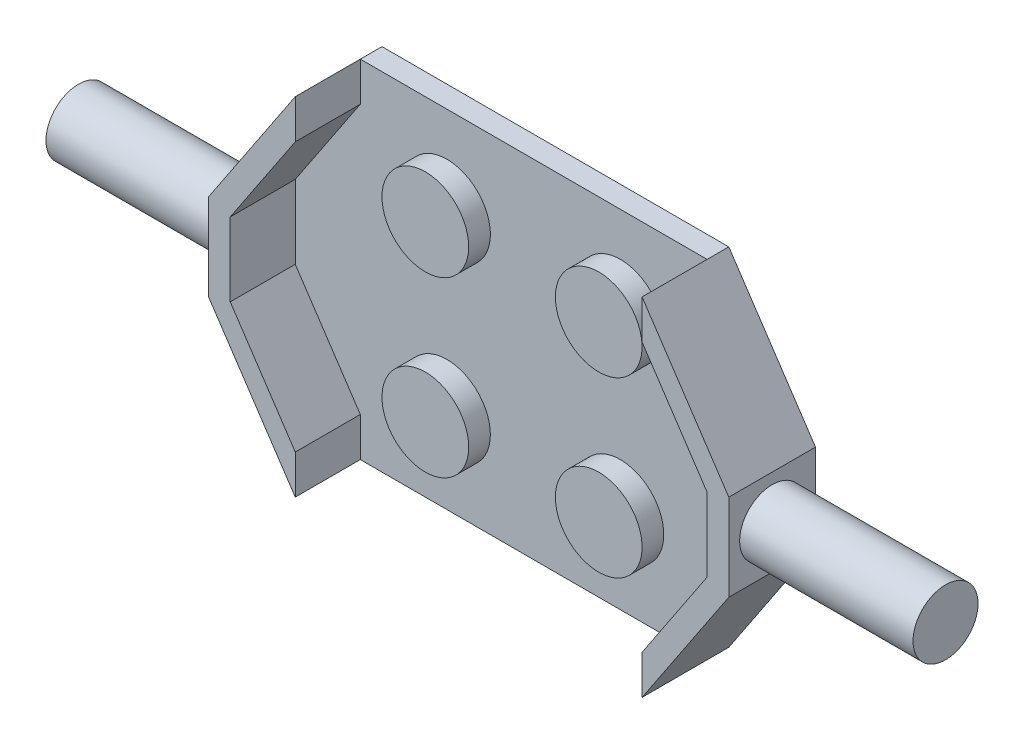
SolidWorks part; units mm, degrees
ref_plane "Front Plane" through (0, 0, 0) normal (0, 0, 1) x (1, 0, 0)
ref_plane "Top Plane" through (0, 0, 0) normal (0, 1, 0) x (1, 0, 0)
ref_plane "Right Plane" through (0, 0, 0) normal (1, 0, 0) x (0, 0, -1)
sketch "Sketch2" plane through (0, 0, 0) normal (0, 0, 1) x (1, 0, 0)
  line L0 (0, 8) -> (0, -8) construction
  line L1 (0, 0) -> (-12, 0) construction
  line L2 (-12, -2) -> (-12, 2)
  line L3 (0, 8) -> (-8, 8)
  line L4 (-8, 8) -> (-12, 2)
  line L5 (0, -8) -> (-8, -8)
  line L6 (-8, -8) -> (-12, -2)
  line L7 (0, 8) -> (0, -8)
  dimension "D1" = 8
  dimension "D2" = 12
  dimension "D3" = 2
  dimension "D4" = 8
extrude "Boss-Extrude1" add sketch "Sketch2" along normal blind 1
sketch "Sketch3" plane through (0, 0, 1) normal (0, 0, 1) x (1, 0, 0)
  line L0 (0, -8) -> (0, 8) construction
  line L1 (0, 8) -> (-8, 8) construction
  line L8 (0, 0) -> (-12, 0)
  line L9 (-12, 2) -> (-12, -2) construction
  circle A0 centre (-4, 4) radius 2
  circle A1 centre (-4, -4) radius 2
  point P8 (-4, 8)
  dimension "D1" = 4
  dimension "D2" = 4
  dimension "D3" = 4
extrude "Boss-Extrude2" add sketch "Sketch3" along normal blind 1 contours A1 | A0
sketch "Sketch4" plane through (0, 0, 1) normal (0, 0, 1) x (1, 0, 0)
  line L0 (-12, -2) -> (-8, -8) construction
  line L1 (-12, 2) -> (-12, -2) construction
  line L2 (-8, 8) -> (-12, 2) construction
  line L3 (-12, -2) -> (-8, -8)
  line L4 (-12, 2) -> (-12, -2)
  line L5 (-8, 8) -> (-12, 2)
  line L6 (-8, 6.1972) -> (-11, 1.6972)
  line L7 (-11, 1.6972) -> (-11, -1.6972)
  line L8 (-11, -1.6972) -> (-8, -6.1972)
  line L9 (-8, 8) -> (-8, 6.1972)
  line L10 (-8, -6.1972) -> (-8, -8)
  line L11 (-7.1679, 7.4453) -> (-11, 1.6972) construction
  line L13 (-11, -1.6972) -> (-7.1679, -7.4453) construction
  dimension "D1" = 1
extrude "Boss-Extrude3" add sketch "Sketch4" along normal blind 3
sketch3d "3DSketch1"
  point P0 (-12, 1.2675, 2.5652)
sketch "Sketch5" plane through (-12, 0, 0) normal (-1, 0, 0) x (0, 0, 1)
  line L0 (0, 0) -> (4, 0) construction
  line L1 (4, 2) -> (4, -2) construction
  circle A0 centre (2, 0) radius 1.5
  dimension "D1" = 3
extrude "Boss-Extrude6" add sketch "Sketch5" along normal blind 8
mirror "Mirror3" about plane through (0, 0, 0) normal (1, 0, 0) of "Boss-Extrude6", "Boss-Extrude3", "Boss-Extrude2", "Boss-Extrude1"
